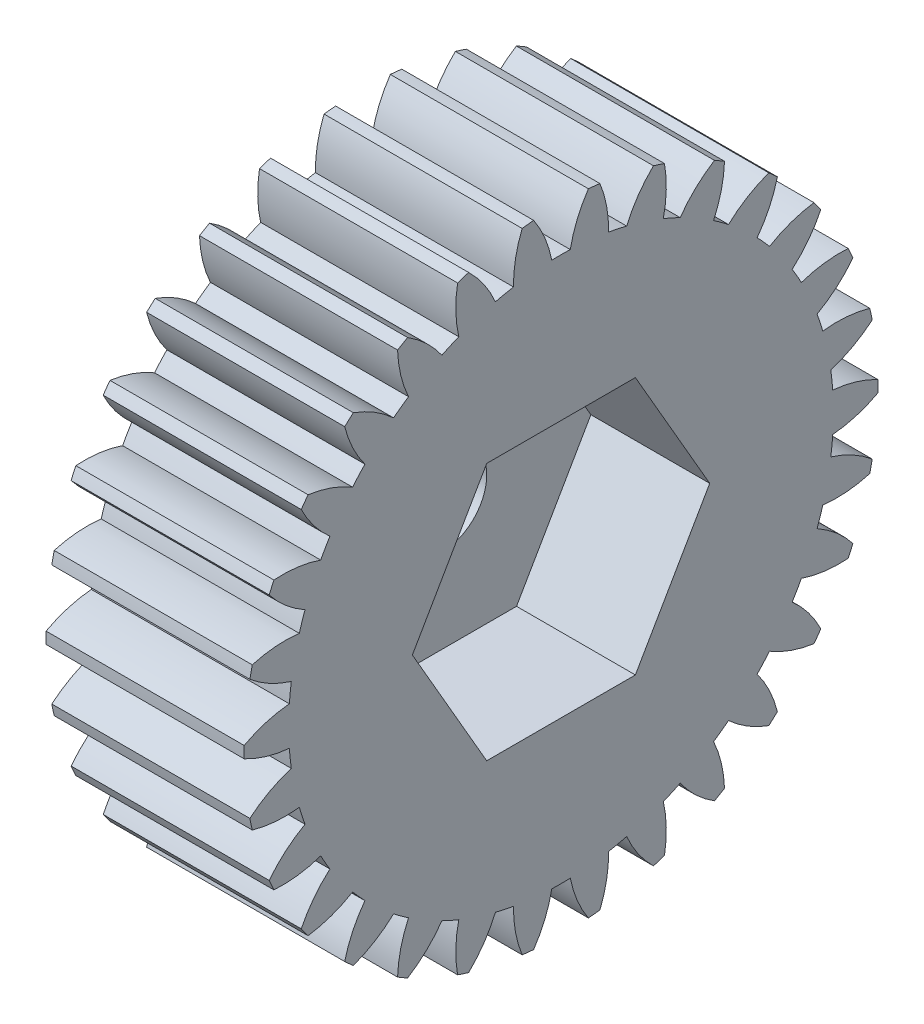
SolidWorks part; units mm, degrees
ref_plane "Plane1" through (0, 0, 0) normal (0, 0, 1) x (1, 0, 0)
ref_plane "Plane2" through (0, 0, 0) normal (0, 1, 0) x (1, 0, 0)
ref_plane "Plane3" through (0, 0, 0) normal (1, 0, 0) x (0, 0, -1)
sketch "HoldingSke" plane through (0, 0, 0) normal (0, 1, 0) x (1, 0, 0)
  line L0 (0, 0) -> (0.866, -0.5)
  line L1 (-15, 0) -> (100, 0) construction
  line L2 (0, 0) -> (-2.1039, 2.3779)
  line L3 (0, 0) -> (-11.863, 4.5341)
  line L4 (0, 0) -> (7.479, 4.318)
  line L5 (0, 0) -> (-46.8476, -17.4728)
  line L6 (0, 0) -> (-8.2896, -5.593)
  line L7 (-2.1039, 2.3779) -> (8.6586, 51.2059)
  line L8 (-76.2, 54.61) -> (-76.1, 54.61)
  line L9 (-71.009, 38.7566) -> (-53.1078, 45.2721)
  line L10 (-76.2, 71.12) -> (104.1128, 71.12)
  line L11 (0, 0) -> (-10, 0)
  line L12 (-76.2, 101.6) -> (-76.162, 101.6)
  line L13 (24.9733, 27.94) -> (52.9518, 28.4284)
  line L14 (24.9733, 27.94) -> (24.9743, 27.94)
  line L15 (24.9733, 27.94) -> (100.4006, 29.5858)
  line L16 (-63.627, -1) -> (-12.827, -1)
  circle A0 centre (0, 0) radius 0.4
  circle A1 centre (0, 0) radius 13.749
  circle A2 centre (0, 0) radius 37.5
  circle A3 centre (0, 0) radius 0.4
  dimension "MHD" = 27.498
  dimension "Hub_dia" = 75
  dimension "Bore" = 0.8
  dimension "MBD" = 0.8
  dimension "Num_teeth" = 30
  dimension "Pitch" = 1
  dimension "Overall_len" = 50
  dimension "Show_teeth" = 30
  dimension "Thickness" = 10
  dimension "OAL" = 50.0001
  dimension "T_dim" = 0.1
  dimension "Ap" = 20
  dimension "H" = 19.05
  dimension "Pitch_radius" = 180.3128
  dimension "Width" = 10
  dimension "Backlash" = 0.038
  dimension "Addendum_fac" = 1
  dimension "Dedendum_fac" = 1.25
  dimension "Clearance_fac" = 0.25
  dimension "Dedendum_add" = 0.001
  dimension "Module" = 1
sketch "BasProSke" plane through (0, 0, 0) normal (0, 1, 0) x (1, 0, 0)
  line L0 (-10, 0) -> (60, 0) construction
  line L1 (0, 0) -> (0, 16)
  line L2 (0, 0) -> (10, 0)
  line L3 (10, 0) -> (10, 16)
  line L4 (10, 16) -> (0, 16)
  dimension "Thickness" = 10
  dimension "Diameter" = 32
revolve "Base-Revolve" add sketch "BasProSke" angle 360 about L0
sketch "TooCutSke" plane through (0, 0, 0) normal (1, 0, 0) x (0, 0, -1)
  line L1 (0, 0) -> (0, 107) construction
  line L2 (0, 0) -> (-0.8515, 14.9758) construction
  line L3 (0, 0) -> (-3.1323, 29.8014) construction
  line L4 (-0.8515, 14.9758) -> (-1.5661, 14.9007) construction
  arc A0 (0.4664, 13.7411) -> (-0.4664, 13.7411) centre (0, 0) ccw
  arc A1 (1.3975, 15.9644) -> (-1.3975, 15.9644) centre (0, 0) ccw
  circle A2 centre (0, 0) radius 15 construction
  circle A3 centre (0, 0) radius 14.0954 construction
  arc A4 (-0.4664, 13.7411) -> (-1.3975, 15.9644) centre (-6.3534, 12.5823) ccw
  arc A5 (1.3975, 15.9644) -> (0.4664, 13.7411) centre (6.3534, 12.5823) ccw
  dimension "Root_dia" = 27.498
  dimension "Overcut_dia" = 32.0508
  dimension "Pitch_dia" = 30
  dimension "Base_dia" = 28.1908
  dimension "Flank_rad" = 6
  dimension "Half_ang" = 6
  dimension "Half_CT" = 0.7185
extrude "ToothCut" cut sketch "TooCutSke" along normal through all
fillet "Breaks" [suppressed] radius 0.02
fillet "RootFillets" [suppressed] radius 0.251
pattern_circular "TeethCuts" count 30 every 12 about axis through (-10, 0, 0) along (1, 0, 0) of "ToothCut", "RootFillets", "Breaks"
sketch "HubNeaOneSke" plane through (0, 0, 0) normal (-1, 0, 0) x (0, 0, 1)
  circle A0 centre (0, 0) radius 13.749
  dimension "Diameter" = 27.498
extrude "HubNearOne" [suppressed] add sketch "HubNeaOneSke" along normal blind 40.0001
sketch "HubNeaBotSke" plane through (0, 0, 0) normal (-1, 0, 0) x (0, 0, 1)
  circle A0 centre (0, 0) radius 13.749
  dimension "Diameter" = 27.498
extrude "HubNearBoth" [suppressed] add sketch "HubNeaBotSke" along normal blind 20
ref_plane "FarPln" through (10, 0, 0) normal (1, 0, 0) x (0, 0, -1)
sketch "HubFarSke" plane through (10, 0, 0) normal (1, 0, 0) x (0, 0, -1)
  circle A0 centre (0, 0) radius 13.749
  dimension "Diameter" = 27.498
extrude "HubFar" [suppressed] add sketch "HubFarSke" along normal blind 20
sketch "BorSke" plane through (0, 0, 0) normal (1, 0, 0) x (0, 0, -1)
  circle A0 centre (0, 0) radius 0.4
  dimension "Diameter" = 0.8
extrude "Bore" cut sketch "BorSke" along normal mid plane 100.0001
sketch "KeySke" plane through (0, 0, 0) normal (1, 0, 0) x (0, 0, -1)
  line L0 (-0.05, 0) -> (-0.05, 0.5)
  line L1 (-0.05, 0.5) -> (0.05, 0.5)
  line L2 (0.05, 0.5) -> (0.05, 0)
  line L3 (0, 0) -> (0, 34) construction
  line L4 (-0.05, 0) -> (0.05, 0)
  dimension "Offset" = 0.5
  dimension "Width" = 0.1
extrude "Keyway" [suppressed] cut sketch "KeySke" along normal mid plane 100.0001
pattern_circular "Keyway2" [suppressed] count 2 every 90 about axis through (-10, 0, 0) along (1, 0, 0)
sketch "Sketch6" plane through (10, 0, 0) normal (1, 0, 0) x (0, 0, -1)
  line L0 (-3.7528, 6.5) -> (3.7528, 6.5)
  line L1 (3.7528, 6.5) -> (7.5056, 0)
  line L2 (7.5056, 0) -> (3.7528, -6.5)
  line L3 (3.7528, -6.5) -> (-3.7528, -6.5)
  line L4 (-3.7528, -6.5) -> (-7.5056, 0)
  line L5 (-7.5056, 0) -> (-3.7528, 6.5)
  point P14 (0, 0)
extrude "Cut-Extrude2" cut sketch "Sketch6" against normal blind 6
sketch "Sketch7" plane through (0, 0, 0) normal (-1, 0, 0) x (0, 0, 1)
  circle A1 centre (0, 0) radius 2.25
  dimension "D1" = 4.5
extrude "Cut-Extrude3" cut sketch "Sketch7" against normal blind 6
equation "' \"Module@HoldingSke\" = 6.35"
equation "' \"Num_teeth@HoldingSke\" = 12"
equation "' \"Ap@HoldingSke\" =  20"
equation "' \"Ap@HoldingSke\" = 20"
equation "' \"Width@HoldingSke\" = 0.5 * 25.4"
equation "' \"Hub_dia@HoldingSke\"= 1 * 25.4"
equation "' \"Hub_dia@HoldingSke\" = 1 * 25.4"
equation "' \"Overall_len@HoldingSke\" = 1.0 * 25.4"
equation "' \"Bore@HoldingSke\" = 0.75 * 25.4"
equation "' \"T_dim@HoldingSke\" = 0.1 * 25.4"
equation "' \"Width@KeySke\" = 0.25 * 25.4"
equation "' \"Show_teeth@HoldingSke\" = 13"
equation "' \"Backlash@HoldingSke\" = 0.009 * 25.4"
equation "' \"Addendum_fac@HoldingSke\" = 1.0"
equation "' \"Dedendum_fac@HoldingSke\" = 1.25"
equation "' \"Dedendum_add@HoldingSke\" = 0.00005 * 25.4"
equation "' \"Clearance_fac@HoldingSke\" = 0.25"
equation "\"Pitch@HoldingSke\" = 1 / \"Module@HoldingSke\""
equation "\"Overcut_dia@TooCutSke\" = (\"Num_teeth@HoldingSke\" + 2 * \"Addendum_fac@HoldingSke\") / \"Pitch@HoldingSke\" + 0.002 * 25.4"
equation "\"Pitch_dia@TooCutSke\" = \"Num_teeth@HoldingSke\" / \"Pitch@HoldingSke\""
equation "\"Base_dia@TooCutSke\" = \"Num_teeth@HoldingSke\" / \"Pitch@HoldingSke\" * cos((\"Ap@HoldingSke\"  * 3.14159265 / 180))"
equation "\"Root_dia@TooCutSke\" = (\"Num_teeth@HoldingSke\" + 2) / \"Pitch@HoldingSke\" - 2 * (\"Addendum_fac@HoldingSke\" + \"Dedendum_fac@HoldingSke\") / \"Pitch@HoldingSke\" - \"Dedendum_add@HoldingSke\" * 2"
equation "\"Half_ang@TooCutSke\" = 180 / \"Num_teeth@HoldingSke\""
equation "\"Half_CT@TooCutSke\" = \"Num_teeth@HoldingSke\" / \"Pitch@HoldingSke\" * sin((3.14159265 / 2 / \"Num_teeth@HoldingSke\")) / 2 - 7 * \"Backlash@HoldingSke\" / 4"
equation "\"Flank_rad@TooCutSke\" = \"Num_teeth@HoldingSke\" / \"Pitch@HoldingSke\" / 5"
equation "\"Radius@RootFillets\" = \"Clearance_fac@HoldingSke\" / \"Pitch@HoldingSke\" + \"Dedendum_add@HoldingSke\""
equation "\"Break_rad@Breaks\" = 0.02 / \"Pitch@HoldingSke\""
equation "\"Thickness@HoldingSke\" = \"Width@HoldingSke\""
equation "\"OAL@HoldingSke\" = \"Thickness@HoldingSke\""
equation "\"MHD@HoldingSke\" = (\"Num_teeth@HoldingSke\" + 2) / \"Pitch@HoldingSke\" - 2 * (\"Addendum_fac@HoldingSke\" + \"Dedendum_fac@HoldingSke\")  / \"Pitch@HoldingSke\" - \"Dedendum_add@HoldingSke\" * 2"
equation "\"MBD@HoldingSke\" = (\"Num_teeth@HoldingSke\" + 2) / \"Pitch@HoldingSke\" - 2 * (\"Addendum_fac@HoldingSke\" + \"Dedendum_fac@HoldingSke\")  / \"Pitch@HoldingSke\" - \"Dedendum_add@HoldingSke\" * 2 - 0.002 * 25.4"
equation "\"MHD@HoldingSke\" = ((sgn( \"MHD@HoldingSke\" - \"Hub_dia@HoldingSke\" )-1)*( \"MHD@HoldingSke\" - \"Hub_dia@HoldingSke\" ))/-2+ \"Hub_dia@HoldingSke\""
equation "\"MBD@HoldingSke\" = ((sgn( \"MBD@HoldingSke\" - \"Bore@HoldingSke\" )-1)*( \"MBD@HoldingSke\" - \"Bore@HoldingSke\" ))/-2+ \"Bore@HoldingSke\""
equation "\"OAL@HoldingSke\" = ((sgn( \"OAL@HoldingSke\" - \"Overall_len@HoldingSke\" )+1)*( \"OAL@HoldingSke\" - \"Overall_len@HoldingSke\" ))/2 + \"Overall_len@HoldingSke\" + 0.000002 * 25.4"
equation "\"Num_teeth@TeethCuts\" = int( \"Show_teeth@HoldingSke\" ) + 1"
equation "\"Num_teeth@TeethCuts\" = ((sgn( \"Num_teeth@TeethCuts\" - \"Num_teeth@HoldingSke\" )-1)*( \"Num_teeth@TeethCuts\" - \"Num_teeth@HoldingSke\" ))/-2+ \"Num_teeth@HoldingSke\""
equation "\"Num_teeth@TeethCuts\" = ((sgn( \"Num_teeth@TeethCuts\" - 2.0)+1)*( \"Num_teeth@TeethCuts\" - 2.0))/2 +2.0"
equation "\"Angle@TeethCuts\" = 360.0 / \"Num_teeth@HoldingSke\""
equation "\"Diameter@BasProSke\" = (\"Num_teeth@HoldingSke\" + 2 * \"Addendum_fac@HoldingSke\") / \"Pitch@HoldingSke\""
equation "\"Thickness@BasProSke\"  = \"Thickness@HoldingSke\""
equation "' \"Fillet_rad@BasProSke\" =  \"Thickness@HoldingSke\" * 0.05"
equation "' \"Fillet_rad@BasProSke\" = \"Thickness@HoldingSke\" * 0.05"
equation "\"MHD@HoldingSke\" = ((sgn( \"MHD@HoldingSke\" - \"Root_dia@TooCutSke\" )-1)*( \"MHD@HoldingSke\" - \"Root_dia@TooCutSke\" ))/-2+ \"Root_dia@TooCutSke\""
equation "\"Diameter@HubNeaOneSke\" = \"MHD@HoldingSke\""
equation "\"Length@HubNearOne\" = \"OAL@HoldingSke\" - \"Thickness@BasProSke\""
equation "\"Diameter@HubNeaBotSke\" = \"MHD@HoldingSke\""
equation "\"Length@HubNearBoth\" = ( \"OAL@HoldingSke\" - \"Thickness@BasProSke\" ) / 2.0"
equation "\"Thickness@FarPln\" = \"Thickness@BasProSke\""
equation "\"Diameter@HubFarSke\" = \"MHD@HoldingSke\""
equation "\"Length@HubFar\" = ( \"OAL@HoldingSke\" - \"Thickness@BasProSke\" ) / 2.0"
equation "\"Diameter@BorSke\" = \"MBD@HoldingSke\""
equation "\"D1@Bore\" = \"OAL@HoldingSke\" * 2.0"
equation "\"D1@Keyway\" = \"OAL@HoldingSke\" * 2.0"
equation "\"Offset@KeySke\" = \"T_dim@HoldingSke\" + \"MBD@HoldingSke\" / 2.0"
